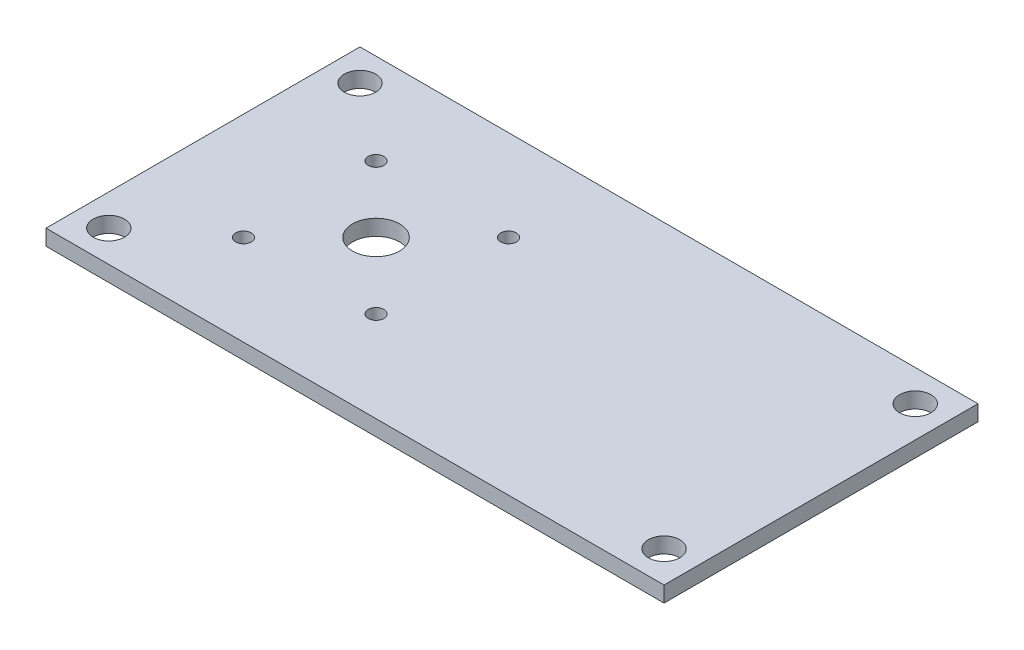
SolidWorks part; units mm, degrees
ref_plane "Front Plane" through (0, 0, 0) normal (0, 0, 1) x (1, 0, 0)
ref_plane "Top Plane" through (0, 0, 0) normal (0, 1, 0) x (1, 0, 0)
ref_plane "Right Plane" through (0, 0, 0) normal (1, 0, 0) x (0, 0, -1)
sketch "Sketch7" plane through (0, 0, 0) normal (0, 1, 0) x (1, 0, 0)
  line L0 (0, 114.3) -> (12.7, 114.3) construction
  line L1 (0, 0) -> (250, 0)
  line L2 (0, 0) -> (0, 127)
  line L3 (0, 127) -> (250, 127)
  line L4 (250, 0) -> (250, 127)
  line L5 (12.7, 114.3) -> (12.7, 127) construction
  line L6 (12.7, 114.3) -> (237.3, 114.3) construction
  line L7 (12.7, 114.3) -> (12.7, 12.7) construction
  line L8 (12.7, 12.7) -> (237.3, 12.7) construction
  line L9 (237.3, 114.3) -> (237.3, 12.7) construction
  line L10 (237.3, 0) -> (237.3, 12.7) construction
  line L11 (237.3, 12.7) -> (250, 12.7) construction
  line L13 (215.25, 8.25) -> (104.75, 8.25) construction
  line L14 (215.25, 8.25) -> (215.25, 118.75) construction
  line L15 (215.25, 118.75) -> (104.75, 118.75) construction
  line L16 (104.75, 8.25) -> (104.75, 118.75) construction
  line L17 (215.25, 8.25) -> (104.75, 118.75) construction
  line L18 (215.25, 118.75) -> (104.75, 8.25) construction
  line L19 (204.45, 19.05) -> (115.55, 19.05) construction
  line L20 (204.45, 19.05) -> (204.45, 107.95) construction
  line L21 (204.45, 107.95) -> (115.55, 107.95) construction
  line L22 (115.55, 19.05) -> (115.55, 107.95) construction
  line L23 (204.45, 19.05) -> (115.55, 107.95) construction
  line L24 (204.45, 107.95) -> (115.55, 19.05) construction
  line L25 (96.8064, 36.6936) -> (43.1936, 36.6936) construction
  line L26 (96.8064, 36.6936) -> (96.8064, 90.3064) construction
  line L27 (96.8064, 90.3064) -> (43.1936, 90.3064) construction
  line L28 (43.1936, 36.6936) -> (43.1936, 90.3064) construction
  line L29 (96.8064, 36.6936) -> (43.1936, 90.3064) construction
  line L30 (96.8064, 90.3064) -> (43.1936, 36.6936) construction
  line L31 (248.2985, 12.7) -> (242.7993, 22.225) construction
  line L32 (242.7993, 22.225) -> (231.8007, 22.225) construction
  line L33 (231.8007, 22.225) -> (226.3015, 12.7) construction
  line L34 (226.3015, 12.7) -> (231.8007, 3.175) construction
  line L35 (231.8007, 3.175) -> (242.7993, 3.175) construction
  line L36 (242.7993, 3.175) -> (248.2985, 12.7) construction
  line L37 (208.2028, 25.55) -> (200.6972, 25.55) construction
  line L38 (200.6972, 25.55) -> (196.9444, 19.05) construction
  line L39 (196.9444, 19.05) -> (200.6972, 12.55) construction
  line L40 (200.6972, 12.55) -> (208.2028, 12.55) construction
  line L41 (208.2028, 12.55) -> (211.9556, 19.05) construction
  line L42 (211.9556, 19.05) -> (208.2028, 25.55) construction
  circle A0 centre (12.7, 114.3) radius 6.35
  circle A1 centre (237.3, 114.3) radius 6.35
  circle A2 centre (237.3, 12.7) radius 6.35 construction
  circle A3 centre (12.7, 12.7) radius 6.35
  circle A4 centre (115.55, 107.95) radius 4
  circle A5 centre (204.45, 107.95) radius 4
  circle A6 centre (204.45, 19.05) radius 4
  circle A7 centre (115.55, 19.05) radius 4
  circle A8 centre (160, 63.5) radius 12.5
  circle A9 centre (43.1936, 90.3064) radius 3.175
  circle A10 centre (96.8064, 90.3064) radius 3.175
  circle A11 centre (96.8064, 36.6936) radius 3.175
  circle A12 centre (43.1936, 36.6936) radius 3.175
  circle A13 centre (70, 63.5) radius 9.525
  circle A14 centre (237.3, 12.7) radius 9.525 construction
  circle A15 centre (204.45, 19.05) radius 6.5 construction
  circle A16 centre (70, 63.5) radius 56 construction
  circle A17 centre (160, 63.5) radius 34 construction
  point P17 (160, 63.5)
  point P24 (250, 63.5)
  point P26 (160, 63.5)
  point P31 (70, 63.5)
  dimension "D1" = 12.7
  dimension "D6" = 8
  dimension "D7" = 25
  dimension "D9" = 6.35
  dimension "D10" = 19.05
  dimension "D16" = 112
  dimension "D17" = 68
  dimension "D2" = 110.5
  dimension "D3" = 127
  dimension "D4" = 250
  dimension "D5" = 88.9
  dimension "D8" = 12.7
  dimension "D11" = 90
  dimension "D12" = 19.05
  dimension "D13" = 13
  dimension "D14" = 70
  dimension "D15" = 37.91
sketch "Sketch1" plane through (0, 0, 0) normal (0, 1, 0) x (1, 0, 0)
  line L0 (0, 0) -> (250, 0) construction
  line L1 (250, 0) -> (250, 127) construction
  line L2 (0, 127) -> (250, 127) construction
  line L3 (0, 0) -> (0, 127) construction
  line L4 (0, 0) -> (250, 0)
  line L5 (250, 0) -> (250, 127)
  line L6 (0, 127) -> (250, 127)
  line L7 (0, 0) -> (0, 127)
extrude "Boss-Extrude1" add sketch "Sketch1" along normal blind 6.35
sketch "Sketch2" plane through (0, 6.35, 0) normal (0, 1, 0) x (1, 0, 0)
  circle A0 centre (237.3, 12.7) radius 6.35 construction
  circle A1 centre (237.3, 114.3) radius 6.35 construction
  circle A2 centre (12.7, 12.7) radius 6.35 construction
  circle A3 centre (12.7, 114.3) radius 6.35 construction
  circle A4 centre (237.3, 12.7) radius 6.35
  circle A5 centre (237.3, 114.3) radius 6.35
  circle A6 centre (12.7, 12.7) radius 6.35
  circle A7 centre (12.7, 114.3) radius 6.35
  circle A8 centre (43.1936, 36.6936) radius 3.175 construction
  circle A9 centre (96.8064, 36.6936) radius 3.175 construction
  circle A10 centre (96.8064, 90.3064) radius 3.175 construction
  circle A11 centre (43.1936, 90.3064) radius 3.175 construction
  circle A12 centre (70, 63.5) radius 9.525 construction
  circle A18 centre (43.1936, 36.6936) radius 3.175
  circle A19 centre (96.8064, 36.6936) radius 3.175
  circle A20 centre (96.8064, 90.3064) radius 3.175
  circle A21 centre (43.1936, 90.3064) radius 3.175
  circle A22 centre (70, 63.5) radius 9.525
extrude "Cut-Extrude1" cut sketch "Sketch2" against normal through all
